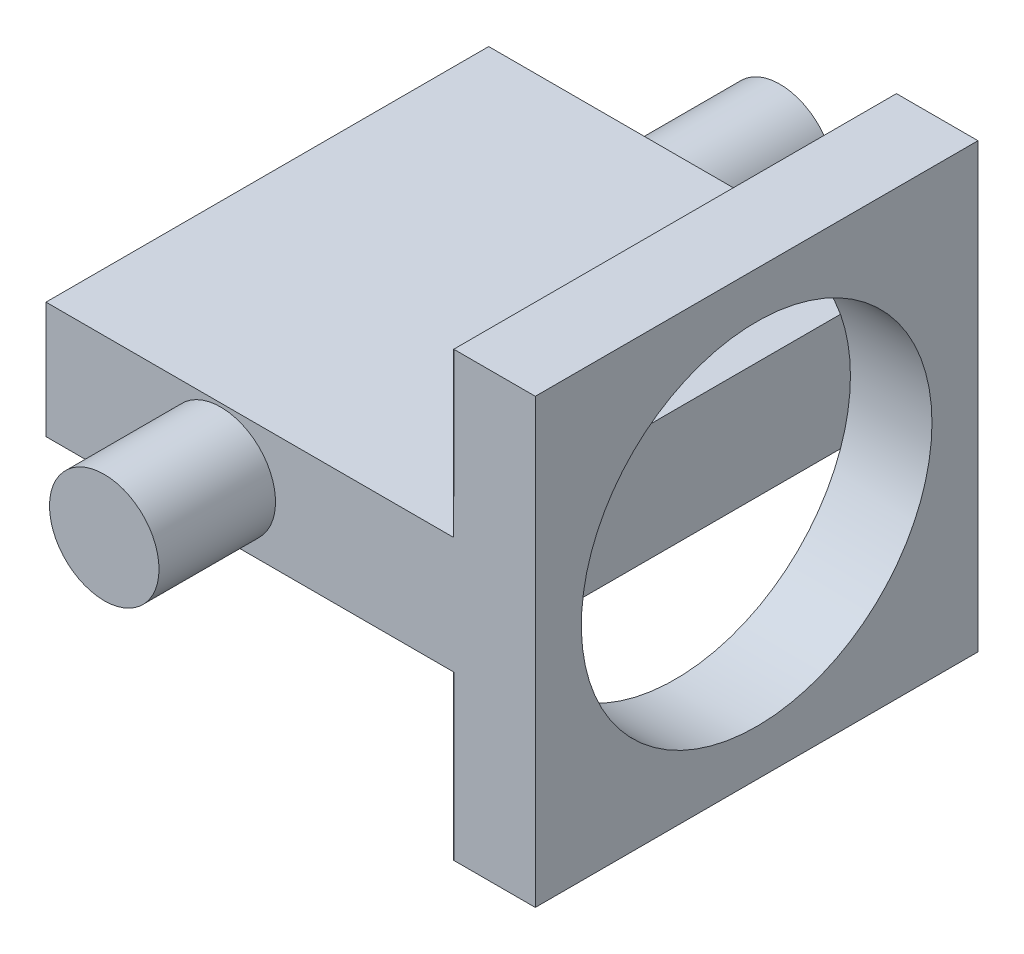
SolidWorks part; units mm, degrees
ref_plane "Front Plane" through (0, 0, 0) normal (0, 0, 1) x (1, 0, 0)
ref_plane "Top Plane" through (0, 0, 0) normal (0, 1, 0) x (1, 0, 0)
ref_plane "Right Plane" through (0, 0, 0) normal (1, 0, 0) x (0, 0, -1)
sketch "Sketch1" plane through (0, 0, 0) normal (1, 0, 0) x (0, 0, -1)
  line L1 (-19, -19) -> (19, -19)
  line L2 (-19, -19) -> (-19, 19)
  line L3 (-19, 19) -> (19, 19)
  line L4 (19, -19) -> (19, 19)
  line L5 (-19, -19) -> (19, 19) construction
  line L6 (-19, 19) -> (19, -19) construction
  circle A0 centre (0, 0) radius 15.05
  dimension "D1" = 30.1
  dimension "D2" = 38
  dimension "D3" = 38
extrude "Boss-Extrude1" add sketch "Sketch1" along normal blind 7
sketch "Sketch2" plane through (0, 0, 0) normal (-1, 0, 0) x (0, 0, 1)
  line L0 (19, 19) -> (19, -19) construction
  line L1 (-19, -5) -> (19, -5)
  line L2 (-19, -5) -> (-19, 5)
  line L3 (-19, 5) -> (19, 5)
  line L4 (19, -5) -> (19, 5)
  line L5 (-19, -5) -> (19, 5) construction
  line L6 (-19, 5) -> (19, -5) construction
  point P0 (0, 0)
  dimension "D1" = 10
extrude "Boss-Extrude2" add sketch "Sketch2" along normal blind 35
sketch "Sketch3" plane through (0, 0, 19) normal (0, 0, 1) x (1, 0, 0)
  line L0 (-35, -5) -> (-35, 5) construction
  circle A0 centre (-20, 0) radius 4.7
  dimension "D2" = 9.4
  dimension "D1" = 15
extrude "Boss-Extrude3" add sketch "Sketch3" along normal blind 10
mirror "Mirror1" about plane through (0, 0, 0) normal (0, 0, 1) of "Boss-Extrude3"
